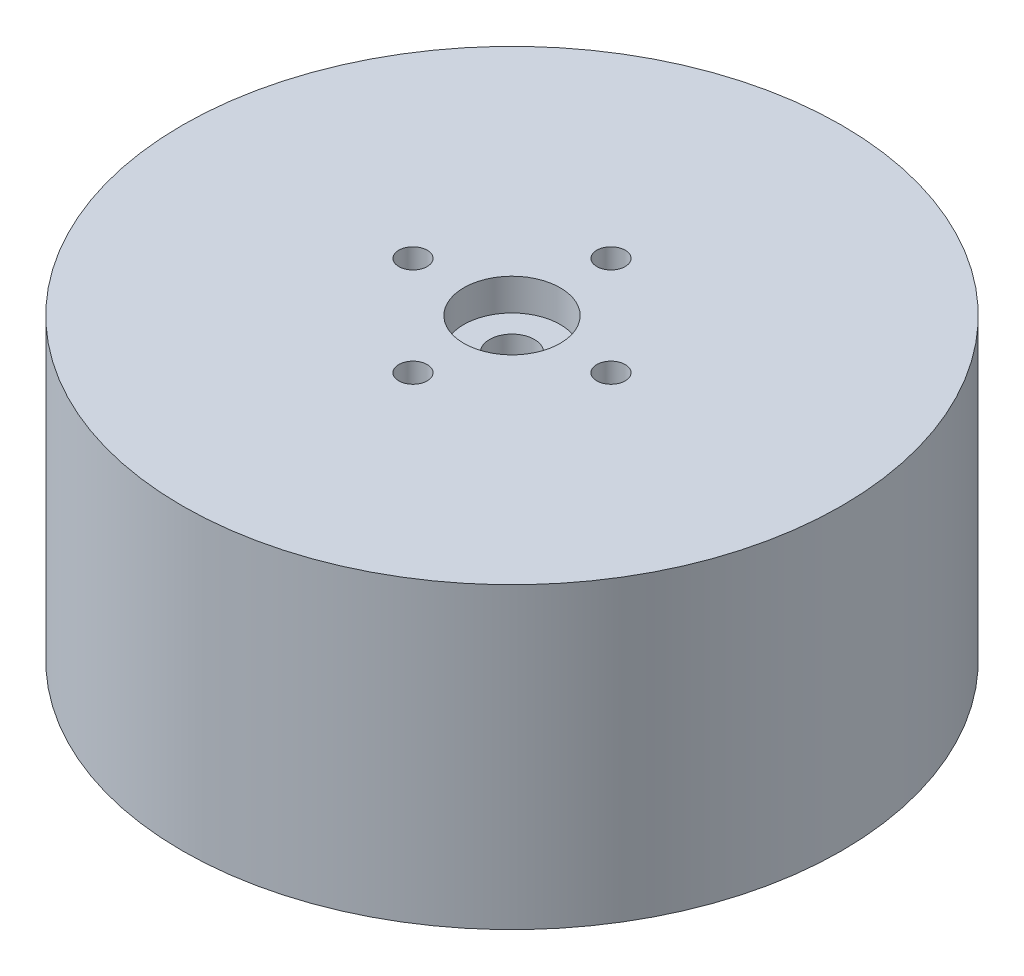
SolidWorks part; units mm, degrees
ref_plane "Front Plane" through (0, 0, 0) normal (0, 0, 1) x (1, 0, 0)
ref_plane "Top Plane" through (0, 0, 0) normal (0, 1, 0) x (1, 0, 0)
ref_plane "Right Plane" through (0, 0, 0) normal (1, 0, 0) x (0, 0, -1)
sketch "Sketch1" plane through (0, 0, 0) normal (0, 1, 0) x (1, 0, 0)
  circle A0 centre (0, 0) radius 38.3
  dimension "D1" = 76.6
extrude "Boss-Extrude1" add sketch "Sketch1" along normal blind 34.7
sketch "Sketch2" plane through (0, 0, 0) normal (0, -1, 0) x (1, 0, 0)
  circle A0 centre (0, 0) radius 2.6
  point P3 (8.8982, 6.7697)
  dimension "D1" = 5.2
extrude "Cut-Extrude2" cut sketch "Sketch2" against normal blind 34.7
sketch "Sketch4" plane through (0, 0, 0) normal (0, -1, 0) x (1, 0, 0)
  circle A0 centre (0, 0) radius 5.6
  dimension "D1" = 11.2
extrude "Cut-Extrude3" cut sketch "Sketch4" against normal blind 3.7
sketch "Sketch5" plane through (0, 34.7, 0) normal (0, 1, 0) x (1, 0, 0)
  circle A0 centre (0, 0) radius 5.6
  dimension "D1" = 11.2
extrude "Cut-Extrude4" cut sketch "Sketch5" against normal blind 3.7
sketch "Sketch6" plane through (0, 34.7, 0) normal (0, 1, 0) x (1, 0, 0)
  line L0 (0, 0) -> (0, 28.1034) construction
  circle A0 centre (0, 11.5) radius 1.65
  circle A1 centre (11.5, 0) radius 1.65
  circle A2 centre (0, -11.5) radius 1.65
  circle A3 centre (-11.5, 0) radius 1.65
  point P14 (0, 0)
  dimension "D1" = 3.3
  dimension "D2" = 11.5
  dimension "D3" = 4
extrude "Cut-Extrude5" cut sketch "Sketch6" against normal through all
